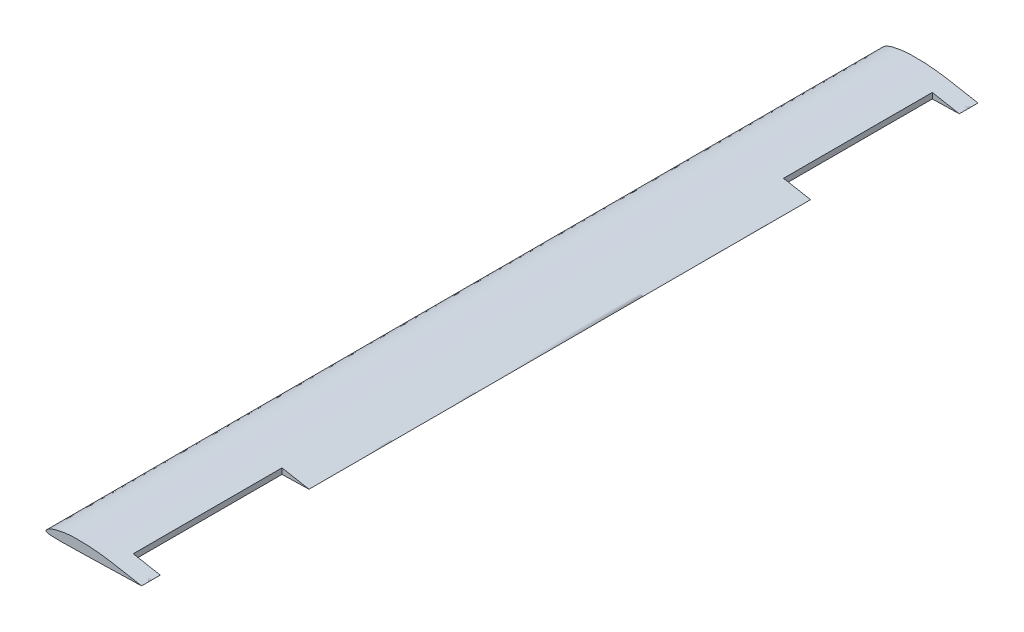
SolidWorks part; units mm, degrees
ref_plane "Front Plane" through (0, 0, 0) normal (0, 0, 1) x (1, 0, 0)
ref_plane "Top Plane" through (0, 0, 0) normal (0, 1, 0) x (1, 0, 0)
ref_plane "Right Plane" through (0, 0, 0) normal (1, 0, 0) x (0, 0, -1)
curve "Curve1"
  spline degree 3 poles (0.9958, -0.0002, 0) (1.001, 0, 0) (0.9959, 0.0004, 0) (0.9918, 0.0012, 0) (0.9819, 0.0027, 0) (0.9699, 0.0048, 0) (0.9542, 0.0075, 0) (0.9358, 0.0109, 0) (0.9145, 0.0148, 0) (0.8908, 0.0194, 0) (0.8648, 0.0244, 0) (0.8367, 0.0299, 0) (0.8069, 0.0358, 0) (0.7756, 0.0418, 0) (0.743, 0.0478, 0) (0.7093, 0.0536, 0) (0.6746, 0.0593, 0) (0.6392, 0.0646, 0) (0.6032, 0.0696, 0) (0.5669, 0.0741, 0) (0.5303, 0.078, 0) (0.4938, 0.0814, 0) (0.4575, 0.084, 0) (0.4216, 0.0859, 0) (0.3863, 0.0872, 0) (0.3516, 0.0876, 0) (0.3179, 0.0873, 0) (0.2852, 0.0862, 0) (0.2537, 0.0842, 0) (0.2236, 0.0815, 0) (0.1949, 0.0781, 0) (0.1678, 0.0739, 0) (0.1424, 0.0692, 0) (0.1188, 0.0638, 0) (0.0972, 0.0579, 0) (0.0776, 0.0516, 0) (0.06, 0.0449, 0) (0.0446, 0.0381, 0) (0.0314, 0.031, 0) (0.0205, 0.024, 0) (0.0118, 0.0172, 0) (0.0054, 0.0106, 0) (0.0016, 0.0048, 0) (-0.0007, -0.0008, 0) (0.0024, -0.0058, 0) (0.0082, -0.0092, 0) (0.0167, -0.0124, 0) (0.0282, -0.0147, 0) (0.0427, -0.0164, 0) (0.0603, -0.0177, 0) (0.0809, -0.0188, 0) (0.1042, -0.0194, 0) (0.1302, -0.02, 0) (0.1586, -0.0201, 0) (0.1892, -0.0202, 0) (0.2219, -0.0198, 0) (0.2565, -0.0194, 0) (0.2927, -0.0185, 0) (0.3303, -0.0176, 0) (0.3692, -0.0166, 0) (0.409, -0.0155, 0) (0.4494, -0.0144, 0) (0.4902, -0.0134, 0) (0.5311, -0.0123, 0) (0.5717, -0.0112, 0) (0.6119, -0.0103, 0) (0.6513, -0.0091, 0) (0.6897, -0.0081, 0) (0.7268, -0.0073, 0) (0.7624, -0.0062, 0) (0.7961, -0.0053, 0) (0.8277, -0.0045, 0) (0.8573, -0.0037, 0) (0.8847, -0.003, 0) (0.9098, -0.0024, 0) (0.9323, -0.0019, 0) (0.9518, -0.0012, 0) (0.9685, -0.0008, 0) (0.9812, -0.0006, 0) (0.9916, -0.0002, 0) (0.9958, -0.0002, 0) (1.001, 0, 0) (0.9959, 0.0004, 0) knots -0.008528 -0.003816 -0.00096 0 0.000951 0.003757 0.008317 0.014522 0.022293 0.03156 0.042221 0.054151 0.067231 0.081331 0.096307 0.112012 0.128327 0.145184 0.162488 0.180136 0.198033 0.216059 0.234134 0.252192 0.270104 0.287817 0.305235 0.322284 0.338896 0.354986 0.370506 0.385417 0.399632 0.413116 0.425823 0.437704 0.448737 0.45888 0.468105 0.476405 0.483748 0.490134 0.495557 0.500012 0.503516 0.506001 0.508215 0.511494 0.515844 0.521547 0.528755 0.537449 0.547575 0.559074 0.571867 0.585873 0.60098 0.61708 0.634081 0.651921 0.670484 0.689642 0.709259 0.729201 0.749303 0.769441 0.789466 0.809254 0.82867 0.847598 0.865915 0.883467 0.900079 0.915618 0.930135 0.943663 0.95605 0.967159 0.976853 0.984996 0.991472 0.996184 0.99904 1 1.000951 1.003757 1.008317 periodic
sketch "Sketch1" plane through (0, 0, 0) normal (0, 0, 1) x (1, 0, 0)
  spline S1 degree 3 poles (149.1678, -0.0309) (150.2077, -0.0064) (149.1856, 0.0796) (148.3623, 0.2385) (146.3836, 0.5358) (143.9755, 0.9628) (140.8452, 1.5091) (137.1575, 2.176) (132.9076, 2.9693) (128.1564, 3.874) (122.95, 4.8879) (117.3393, 5.9846) (111.3795, 7.1508) (105.1224, 8.3627) (98.6041, 9.5664) (91.8579, 10.7273) (84.9242, 11.8625) (77.8367, 12.9284) (70.6388, 13.9152) (63.3717, 14.8201) (56.0682, 15.5996) (48.7695, 16.2706) (41.5085, 16.8046) (34.325, 17.1876) (27.2525, 17.4374) (20.3254, 17.5241) (13.5782, 17.4537) (7.0418, 17.2312) (0.7441, 16.8428) (-5.2871, 16.3024) (-11.0261, 15.6192) (-16.4429, 14.786) (-21.519, 13.8367) (-26.2304, 12.7634) (-30.5573, 11.5855) (-34.484, 10.3237) (-37.9928, 8.9896) (-41.0735, 7.6116) (-43.713, 6.2077) (-45.9013, 4.7987) (-47.6312, 3.4329) (-48.9187, 2.1223) (-49.6801, 0.9599) (-50.1484, -0.1551) (-49.5243, -1.167) (-48.3626, -1.8422) (-46.665, -2.4855) (-44.3631, -2.9499) (-41.4511, -3.2787) (-37.931, -3.5468) (-33.8249, -3.7681) (-29.1585, -3.888) (-23.9658, -3.9969) (-18.2827, -4.0237) (-12.1512, -4.0325) (-5.6138, -3.9608) (1.2939, -3.8709) (8.5341, -3.6968) (16.0669, -3.521) (23.8402, -3.3213) (31.8, -3.0988) (39.8876, -2.8724) (48.047, -2.6865) (56.2167, -2.4608) (64.3437, -2.2341) (72.3738, -2.0501) (80.2537, -1.8173) (87.9351, -1.6172) (95.3645, -1.4519) (102.4785, -1.2397) (109.2165, -1.0613) (115.5436, -0.9076) (121.4518, -0.7409) (126.9334, -0.6016) (131.952, -0.4863) (136.4547, -0.3711) (140.3684, -0.2405) (143.6923, -0.1607) (146.2403, -0.1176) (148.3132, -0.0351) (149.1678, -0.0309) (150.2077, -0.0064) (149.1856, 0.0796) knots -0.008528 -0.003816 -0.00096 0 0.000951 0.003757 0.008317 0.014522 0.022293 0.03156 0.042221 0.054151 0.067231 0.081331 0.096307 0.112012 0.128327 0.145184 0.162488 0.180136 0.198033 0.216059 0.234134 0.252192 0.270104 0.287817 0.305235 0.322284 0.338896 0.354986 0.370506 0.385417 0.399632 0.413116 0.425823 0.437704 0.448737 0.45888 0.468105 0.476405 0.483748 0.490134 0.495557 0.500012 0.503516 0.506001 0.508215 0.511494 0.515844 0.521547 0.528755 0.537449 0.547575 0.559074 0.571867 0.585873 0.60098 0.61708 0.634081 0.651921 0.670484 0.689642 0.709259 0.729201 0.749303 0.769441 0.789466 0.809254 0.82867 0.847598 0.865915 0.883467 0.900079 0.915618 0.930135 0.943663 0.95605 0.967159 0.976853 0.984996 0.991472 0.996184 0.99904 1 1.000951 1.003757 1.008317 only from (150, 0) to (150, 0)
  dimension "D1" = 150
extrude "Boss-Extrude1" add sketch "Sketch1" along normal mid plane 1750 contours S1
sketch "Sketch2" plane through (0, 0, 0) normal (0, 1, 0) x (1, 0, 0)
  line L1 (-40.3803, -54.2778) -> (40.3803, -54.2778)
  line L2 (-40.3803, -54.2778) -> (-40.3803, 54.2778)
  line L3 (-40.3803, 54.2778) -> (40.3803, 54.2778)
  line L4 (40.3803, -54.2778) -> (40.3803, 54.2778)
  line L5 (-40.3803, -54.2778) -> (40.3803, 54.2778) construction
  line L6 (-40.3803, 54.2778) -> (40.3803, -54.2778) construction
  point P0 (0, 0)
extrude "Boss-Extrude2" add sketch "Sketch2" against normal blind 10
sketch "Sketch3" plane through (0, 0, 0) normal (0, 1, 0) x (1, 0, 0)
  line L0 (0, 0) -> (0, 400) construction
  line L2 (-37.2811, 378.2619) -> (37.2811, 378.2619)
  line L3 (-37.2811, 378.2619) -> (-37.2811, 421.7381)
  line L4 (-37.2811, 421.7381) -> (37.2811, 421.7381)
  line L5 (37.2811, 378.2619) -> (37.2811, 421.7381)
  line L6 (-37.2811, 378.2619) -> (37.2811, 421.7381) construction
  line L7 (-37.2811, 421.7381) -> (37.2811, 378.2619) construction
  dimension "D1" = 400
extrude "Boss-Extrude3" add sketch "Sketch3" against normal blind 10
mirror "Mirror1" about plane through (0, 0, 0) normal (0, 0, 1) of "Boss-Extrude3"
sketch "Sketch4" plane through (0, 0, 0) normal (0, 1, 0) x (1, 0, 0)
  line L0 (150, -875) -> (150, 875) construction
  line L1 (150, 835.8776) -> (93.4519, 835.8776)
  line L2 (150, 835.8776) -> (150, 524.6851)
  line L3 (150, 524.6851) -> (93.4519, 524.6851)
  line L4 (93.4519, 835.8776) -> (93.4519, 524.6851)
extrude "Cut-Extrude1" cut sketch "Sketch4" against normal through all both and the other way through all
mirror "Mirror2" about plane through (0, 0, 0) normal (0, 0, 1) of "Cut-Extrude1"
